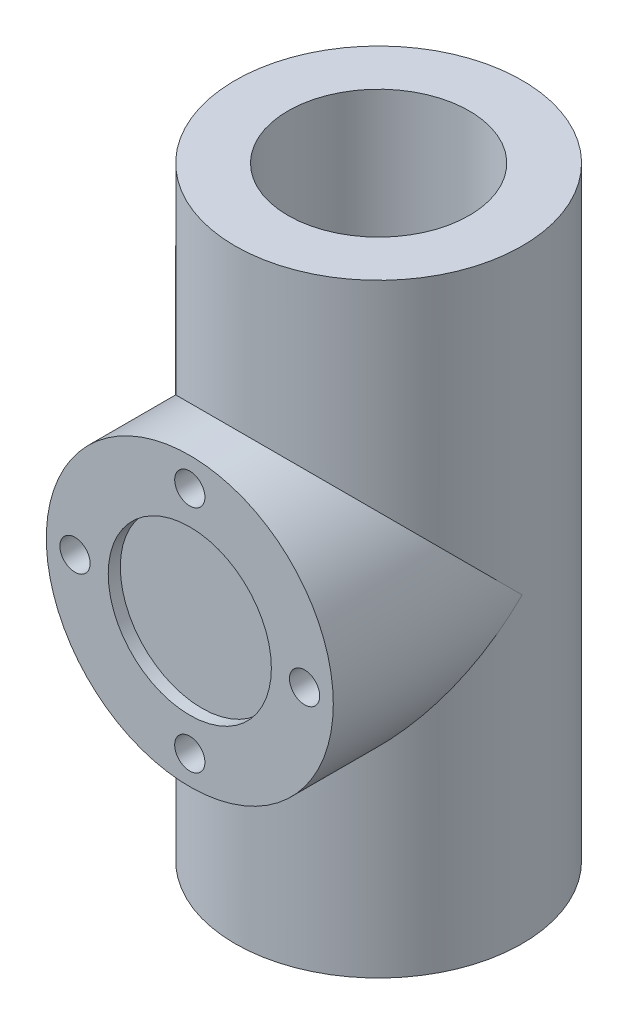
SolidWorks part; units mm, degrees
ref_plane "Front Plane" through (0, 0, 0) normal (0, 0, 1) x (1, 0, 0)
ref_plane "Top Plane" through (0, 0, 0) normal (0, 1, 0) x (1, 0, 0)
ref_plane "Right Plane" through (0, 0, 0) normal (1, 0, 0) x (0, 0, -1)
sketch "Sketch1" plane through (0, 0, 0) normal (0, 1, 0) x (1, 0, 0)
  circle A0 centre (0, 0) radius 47.5
  circle A1 centre (0, 0) radius 30
  dimension "D1" = 95
  dimension "D2" = 60
extrude "Boss-Extrude1" add sketch "Sketch1" along normal blind 200 contours A0
sketch "Sketch2" plane through (0, 200, 0) normal (0, 1, 0) x (1, 0, 0)
  circle A0 centre (0, 0) radius 30
  dimension "D1" = 60
extrude "Cut-Extrude2" cut sketch "Sketch2" against normal blind 200
sketch "Sketch4" plane through (0, 0, 0) normal (0, 0, 1) x (1, 0, 0)
  circle A0 centre (0, 100) radius 47.5
  dimension "D1" = 95
extrude "Boss-Extrude2" add sketch "Sketch4" along normal blind 62.5
sketch "Sketch5" plane through (0, 0, 62.5) normal (0, 0, 1) x (1, 0, 0)
  circle A0 centre (0, 100) radius 38 construction
  circle A1 centre (0, 138) radius 5
  circle A2 centre (0, 62) radius 5
  circle A3 centre (38, 100) radius 5
  circle A4 centre (-38, 100) radius 5
  dimension "D1" = 76
  dimension "D2" = 10
  dimension "D3" = 10
  dimension "D4" = 10
  dimension "D5" = 10
extrude "Cut-Extrude3" cut sketch "Sketch5" against normal blind 20
sketch "Sketch6" plane through (0, 0, 62.5) normal (0, 0, 1) x (1, 0, 0)
  circle A0 centre (0, 100) radius 27
  dimension "D1" = 54
extrude "Cut-Extrude4" cut sketch "Sketch6" against normal blind 4
